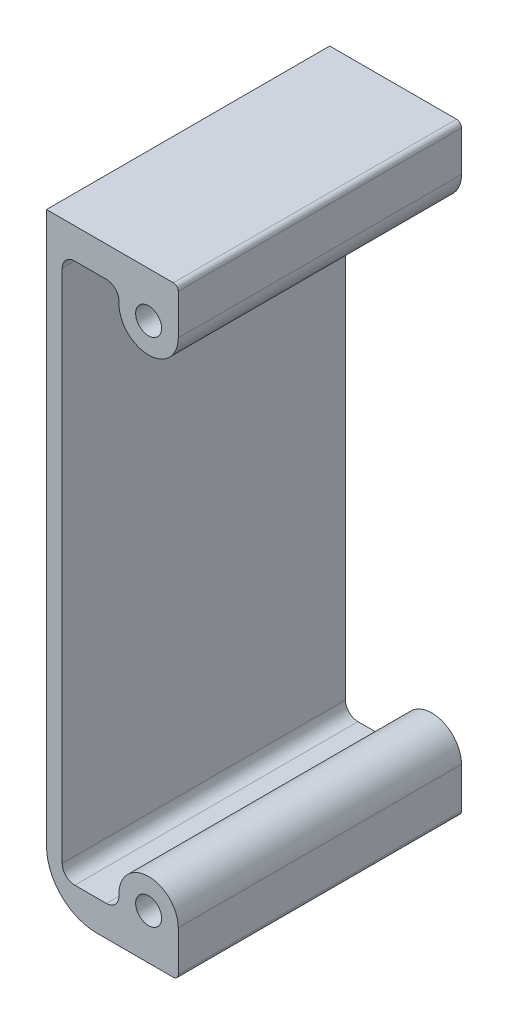
SolidWorks part; units mm, degrees
material "ABS"
ref_plane "X-Y Datum" through (0, 0, 0) normal (0, 0, 1) x (1, 0, 0)
ref_plane "X-Z Datum" through (0, 0, 0) normal (0, 1, 0) x (1, 0, 0)
ref_plane "Y-Z Datum" through (0, 0, 0) normal (1, 0, 0) x (0, 0, -1)
sketch "Sketch1" plane through (0, 0, 0) normal (0, 0, 1) x (1, 0, 0)
  line L0 (26.7441, -45.3716) -> (26.7441, -48.3714)
  line L1 (12.0836, -54.5461) -> (12.0836, 67.1609)
  line L2 (32.7436, -54.5461) -> (12.0836, -54.5461)
  line L3 (38.7431, -45.3716) -> (38.7431, -54.5461)
  line L4 (38.7431, -54.5461) -> (32.7436, -54.5461)
  line L5 (15.2586, 60.9861) -> (15.2586, -48.3714)
  line L7 (32.7436, 57.9864) -> (32.7436, -45.3716) construction
  line L8 (32.7436, 6.3074) -> (18.3664, 6.3074) construction
  line L9 (38.7431, 57.9864) -> (38.7431, 67.1609)
  line L10 (38.7431, 67.1609) -> (32.7436, 67.1609)
  line L11 (32.7436, 67.1609) -> (12.0836, 67.1609)
  line L13 (26.7441, 57.9864) -> (26.7441, 60.9861)
  line L14 (26.7441, -48.3714) -> (15.2586, -48.3714)
  line L15 (26.7441, 60.9861) -> (15.2586, 60.9861)
  arc A0 (38.7431, -45.3716) -> (26.7441, -45.3716) centre (32.7436, -45.3716) ccw
  circle A1 centre (32.7436, -45.3716) radius 2.6251
  arc A2 (38.7431, 57.9864) -> (26.7441, 57.9864) centre (32.7436, 57.9864) cw
  circle A3 centre (32.7436, 57.9864) radius 2.6289
extrude "Boss-Extrude1" add sketch "Sketch1" along normal blind 57.3024
fillet "Fillet1" radius 2.54 4 edges at (26.7441, 60.9861, 28.6512) (15.2586, 60.9861, 28.6512) (26.7441, -48.3714, 28.6512) (15.2586, -48.3714, 28.6512)
fillet "Fillet2" radius 1 2 edges at (38.7431, 67.1609, 28.6512) (38.7431, -54.5461, 28.6512)
fillet "Fillet3" radius 10.16 1 edges at (12.0836, -54.5461, 28.6512)
